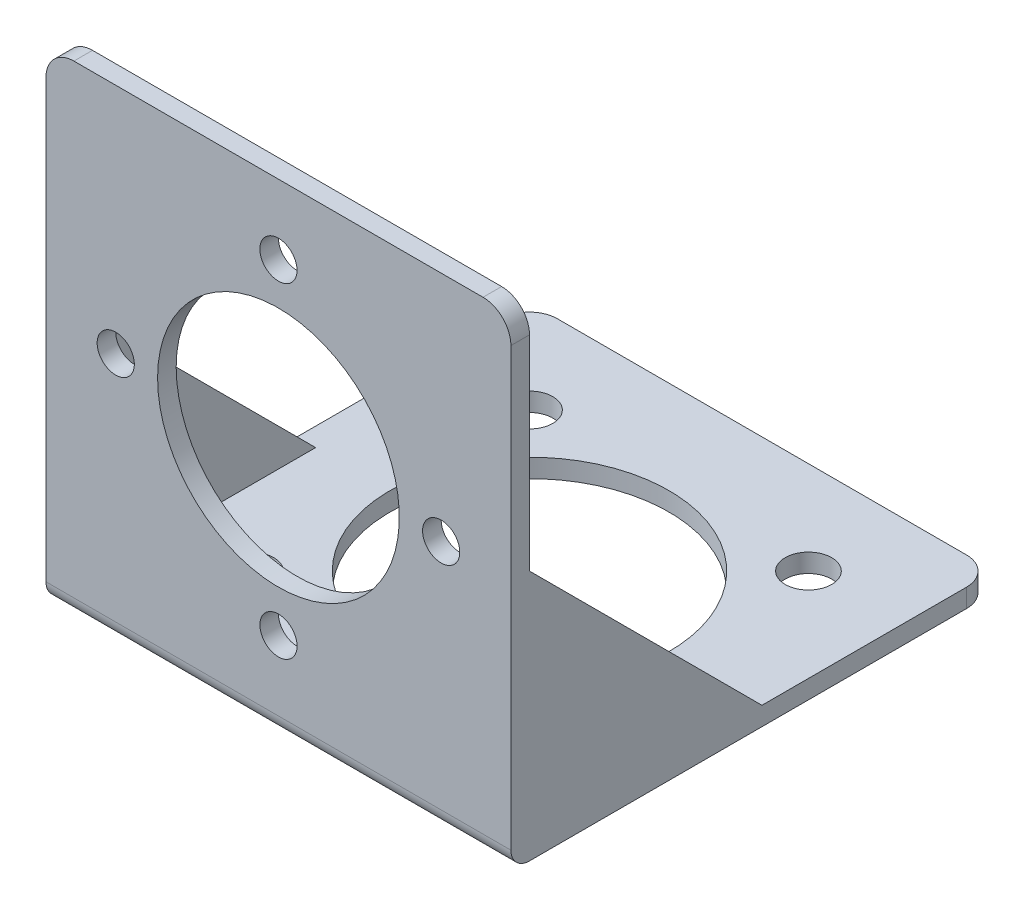
SolidWorks part; units mm, degrees
ref_plane "前视基准面" through (0, 0, 0) normal (0, 0, 1) x (1, 0, 0)
ref_plane "上视基准面" through (0, 0, 0) normal (0, 1, 0) x (1, 0, 0)
ref_plane "右视基准面" through (0, 0, 0) normal (1, 0, 0) x (0, 0, -1)
ref_plane "基准面4" through (46.1387, 0, 0) normal (-1, 0, 0) x (0, -1, 0)
sketch "草图1" plane through (46.1387, 0, 0) normal (-1, 0, 0) x (0, -1, 0)
  line L0 (-27, -84.334) -> (-2, -109.334)
  line L1 (-2, -109.334) -> (-2, -84.334)
  line L2 (-2, -84.334) -> (-27, -84.334)
extrude "凸台-拉伸1" add sketch "草图1" against normal blind 50
sketch "草图2" plane through (0, 2, 0) normal (0, -1, 0) x (1, 0, 0)
  line L0 (46.1387, -84.334) -> (96.1387, -84.334)
  line L1 (96.1387, -84.334) -> (96.1387, -134.334)
  line L2 (96.1387, -134.334) -> (46.1387, -134.334)
  line L3 (46.1387, -134.334) -> (46.1387, -84.334)
extrude "凸台-拉伸2" add sketch "草图2" along normal blind 2
ref_plane "基准面5" through (48.1387, 0, 0) normal (-1, 0, 0) x (0, -1, 0)
sketch "草图3" plane through (48.1387, 0, 0) normal (-1, 0, 0) x (0, -1, 0)
  line L0 (-2, -84.334) -> (-27, -84.334)
  line L1 (-27, -84.334) -> (-2, -109.334)
  line L2 (-2, -109.334) -> (-2, -84.334)
extrude "切除-拉伸1" cut sketch "草图3" against normal blind 46
sketch "草图4" plane through (0, 0, -84.334) normal (0, 0, 1) x (1, 0, 0)
  line L0 (46.1387, 52) -> (96.1387, 52)
  line L1 (96.1387, 52) -> (96.1387, 0)
  line L2 (96.1387, 0) -> (46.1387, 0)
  line L3 (46.1387, 0) -> (46.1387, 52)
extrude "凸台-拉伸3" add sketch "草图4" along normal blind 2
hole_wizard "M22 间隙孔1" positions "草图6" profile "草图5" hole size "M22" standard "ANSI Metric" end condition through all
sketch "草图6" plane through (0, 0, -84.334) normal (0, 0, -1) x (-1, 0, 0)
  line L0 (-71.1387, 52) -> (-71.1387, 27)
  line L1 (-96.1387, 52) -> (-46.1387, 52) construction
  point P0 (-71.1387, 27)
sketch "草图5" plane through (71.1387, 27, -84.334) normal (1, 0, 0) x (0, 1, 0)
  line L0 (0, 0) -> (0, 2)
  line L1 (0, 2) -> (13, 2)
  line L2 (13, 2) -> (13, 0)
  line L5 (13, 0) -> (0, 0)
  line L11 (0, -6.35) -> (0, 107.95) construction
  dimension "通孔孔直径" = 26
  dimension "通孔孔深度" = 2
hole_wizard "Ø4.0 (4) 直径孔1" positions "草图8" profile "草图7" hole size "Ø4.0" standard "ANSI Metric" end condition through all
sketch "草图8" plane through (0, 0, -84.334) normal (0, 0, -1) x (-1, 0, 0)
  line L0 (-71.1387, 52) -> (-71.1387, 44.5)
  line L1 (-96.1387, 52) -> (-46.1387, 52) construction
  point P3 (-71.1387, 44.5)
sketch "草图7" plane through (71.1387, 44.5, -84.334) normal (1, 0, 0) x (0, 1, 0)
  line L0 (0, 0) -> (0, 2)
  line L1 (0, 2) -> (2, 2)
  line L2 (2, 2) -> (2, 0)
  line L5 (2, 0) -> (0, 0)
  line L11 (0, -6.35) -> (0, 107.95) construction
  dimension "通孔孔直径" = 4
  dimension "通孔孔深度" = 2
hole_wizard "M27 间隙孔1" positions "草图10" profile "草图9" hole size "M27" standard "ANSI Metric" end condition through all
sketch "草图10" plane through (0, 2, 0) normal (0, 1, 0) x (1, 0, 0)
  line L0 (48.1387, 109.334) -> (94.1387, 109.334)
  point P0 (71.1387, 109.334)
sketch "草图9" plane through (71.1387, 2, -109.334) normal (1, 0, 0) x (0, 0, 1)
  line L0 (0, 0) -> (0, 2)
  line L1 (0, 2) -> (15, 2)
  line L2 (15, 2) -> (15, 0)
  line L5 (15, 0) -> (0, 0)
  line L11 (0, -6.35) -> (0, 107.95) construction
  dimension "通孔孔直径" = 30
  dimension "通孔孔深度" = 2
hole_wizard "Ø5.0 (5) 直径孔1" positions "草图12" profile "草图11" hole size "Ø5.0" standard "ANSI Metric" end condition through all
sketch "草图12" plane through (0, 2, 0) normal (0, 1, 0) x (1, 0, 0)
  line L0 (56.6387, 134.334) -> (56.6387, 124.334)
  line L1 (46.1387, 134.334) -> (96.1387, 134.334) construction
  line L3 (46.1387, 117.721) -> (56.1387, 117.721)
  line L4 (46.1387, 109.334) -> (46.1387, 134.334) construction
  point P0 (56.1387, 124.334)
sketch "草图11" plane through (56.1387, 2, -124.334) normal (1, 0, 0) x (0, 0, 1)
  line L0 (0, 0) -> (0, 2)
  line L1 (0, 2) -> (2.5, 2)
  line L2 (2.5, 2) -> (2.5, 0)
  line L5 (2.5, 0) -> (0, 0)
  line L11 (0, -6.35) -> (0, 107.95) construction
  dimension "通孔孔直径" = 5
  dimension "通孔孔深度" = 2
fillet "圆角1" radius 2 1 edges at (71.1387, 0, -82.334)
fillet "圆角2" radius 3 4 edges at (96.1387, 52, -83.334) (96.1387, 1, -134.334) (46.1387, 52, -83.334) (46.1387, 1, -134.334)
pattern_circular "阵列(圆周)1" count 4 every 90 about axis through (71.1387, 0, -109.334) along (0, 1, 0) of "Ø5.0 (5) 直径孔1"
pattern_circular "阵列(圆周)2" count 4 every 90 about axis through (71.1387, 27, 0) along (0, 0, 1) of "Ø4.0 (4) 直径孔1"
